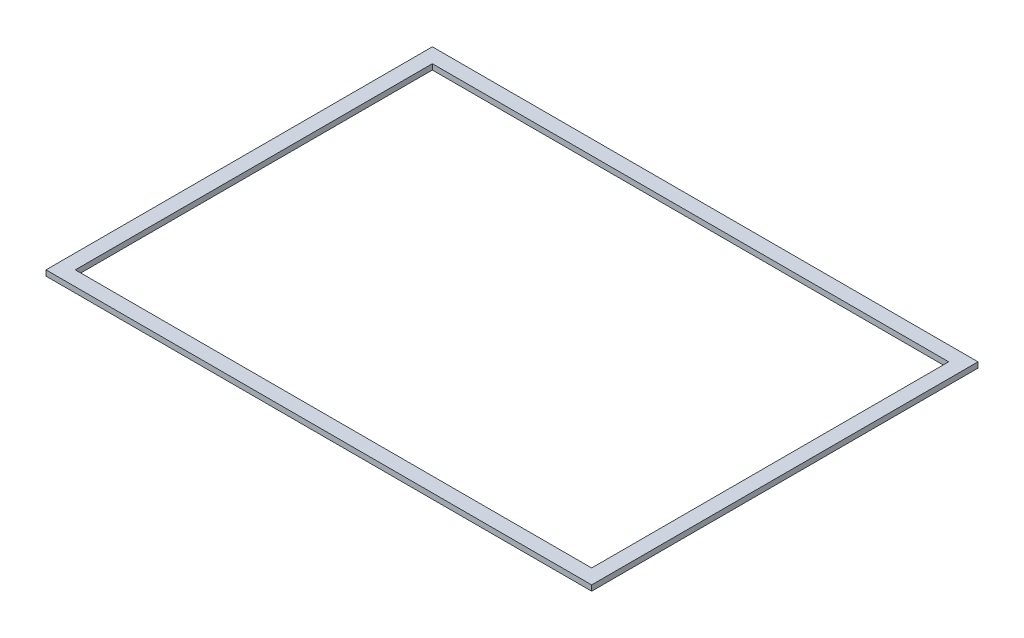
SolidWorks part; units mm, degrees
ref_plane "Front Plane" through (0, 0, 0) normal (0, 0, 1) x (1, 0, 0)
ref_plane "Top Plane" through (0, 0, 0) normal (0, 1, 0) x (1, 0, 0)
ref_plane "Right Plane" through (0, 0, 0) normal (1, 0, 0) x (0, 0, -1)
sketch "Sketch2" plane through (0, 0, 0) normal (0, 1, 0) x (1, 0, 0)
  line L1 (-141, -97.5) -> (141, -97.5)
  line L2 (-141, -97.5) -> (-141, 97.5)
  line L3 (-141, 97.5) -> (141, 97.5)
  line L4 (141, -97.5) -> (141, 97.5)
  line L5 (-141, -97.5) -> (141, 97.5) construction
  line L6 (-141, 97.5) -> (141, -97.5) construction
  line L7 (-149, -105.5) -> (149, -105.5)
  line L8 (-149, -105.5) -> (-149, 105.5)
  line L9 (-149, 105.5) -> (149, 105.5)
  line L10 (149, -105.5) -> (149, 105.5)
  line L11 (-149, -105.5) -> (149, 105.5) construction
  line L12 (-149, 105.5) -> (149, -105.5) construction
  point P0 (0, 0)
  point P6 (0, 0)
  dimension "D1" = 298
  dimension "D2" = 211
  dimension "D3" = 282
  dimension "D4" = 195
extrude "Extrude1" add sketch "Sketch2" along normal blind 3
